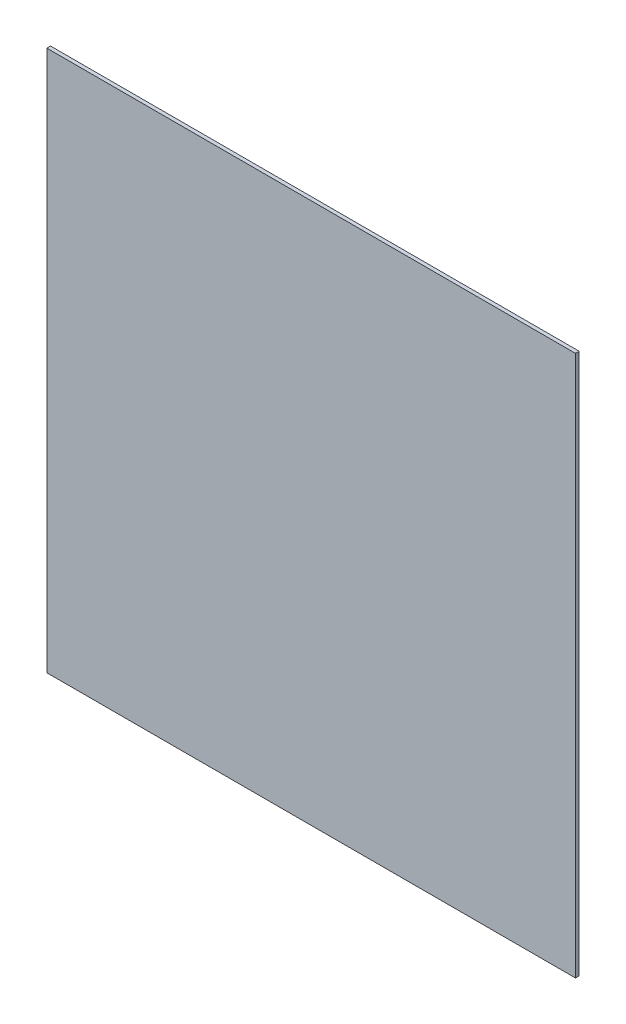
SolidWorks part; units mm, degrees
ref_plane "Front Plane" through (0, 0, 0) normal (0, 0, 1) x (1, 0, 0)
ref_plane "Top Plane" through (0, 0, 0) normal (0, 1, 0) x (1, 0, 0)
ref_plane "Right Plane" through (0, 0, 0) normal (1, 0, 0) x (0, 0, -1)
sketch "Sketch1" plane through (0, 0, 0) normal (0, 0, 1) x (1, 0, 0)
  line L0 (0, 427.6735) -> (0, 0) construction
  line L1 (0, 0) -> (427.6735, 0) construction
  line L3 (-215, 220) -> (215, 220)
  line L4 (-215, 220) -> (-215, -220)
  line L5 (-215, -220) -> (215, -220)
  line L6 (215, 220) -> (215, -220)
  dimension "D1" = 440
  dimension "D2" = 430
extrude "Boss-Extrude1" add sketch "Sketch1" along normal blind 3
